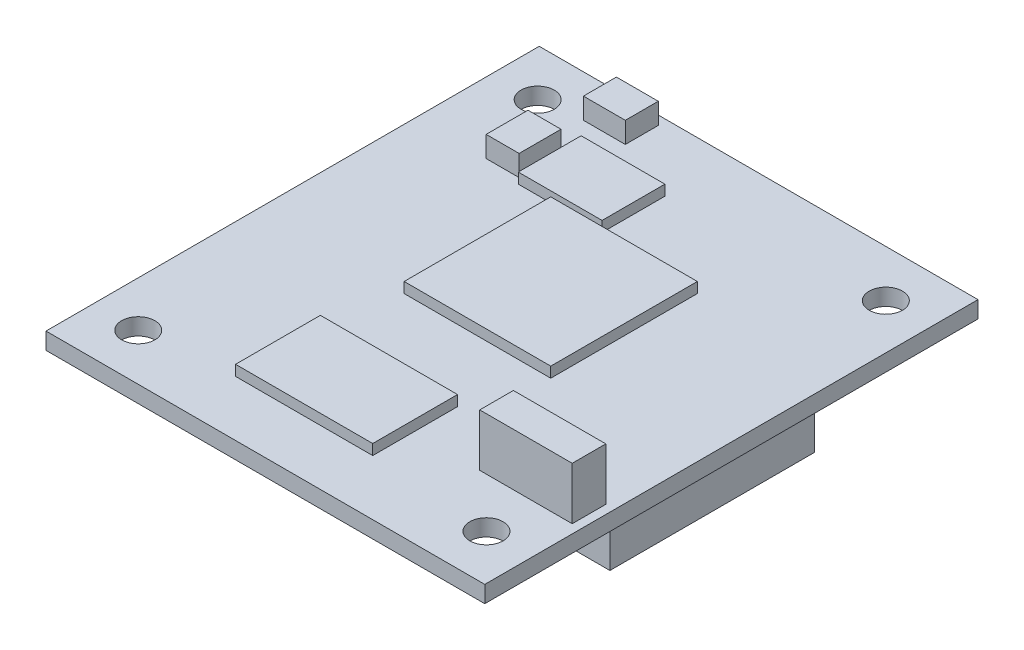
SolidWorks part; units mm, degrees
ref_plane "前视基准面" through (0, 0, 0) normal (0, 0, 1) x (1, 0, 0)
ref_plane "上视基准面" through (0, 0, 0) normal (0, 1, 0) x (1, 0, 0)
ref_plane "右视基准面" through (0, 0, 0) normal (1, 0, 0) x (0, 0, -1)
sketch "草图1" plane through (0, 0, 0) normal (0, 1, 0) x (1, 0, 0)
  line L0 (0, 4.47) -> (41.9, 4.47) construction
  line L1 (0, 0) -> (41.9, 0)
  line L2 (0, 0) -> (0, 47.1)
  line L3 (0, 47.1) -> (41.9, 47.1)
  line L4 (41.9, 0) -> (41.9, 47.1)
  line L5 (0, 42.61) -> (41.9, 42.61) construction
  line L6 (4.34, 47.1) -> (4.34, 0) construction
  line L7 (37.59, 47.1) -> (37.59, 0) construction
  circle A0 centre (4.34, 42.61) radius 1.5875
  circle A1 centre (37.59, 42.61) radius 1.5875
  circle A2 centre (37.59, 4.47) radius 1.5875
  circle A3 centre (4.34, 4.47) radius 1.5875
  dimension "D7" = 3.175
  dimension "D8" = 3.175
  dimension "D9" = 3.175
  dimension "D10" = 3.175
  dimension "D1" = 47.1
  dimension "D2" = 41.9
  dimension "D3" = 4.34
  dimension "D4" = 4.31
  dimension "D5" = 4.47
  dimension "D6" = 4.49
extrude "凸台-拉伸1" add sketch "草图1" along normal blind 1.6
sketch "草图2" plane through (0, 1.6, 0) normal (0, 1, 0) x (1, 0, 0)
  line L0 (0, 0) -> (41.9, 0) construction
  line L1 (6.75, 39.28) -> (9.9, 39.28)
  line L2 (6.75, 39.28) -> (6.75, 35.28)
  line L3 (6.75, 35.28) -> (9.9, 35.28)
  line L4 (9.9, 39.28) -> (9.9, 35.28)
  line L5 (0, 47.1) -> (0, 0) construction
  line L7 (8.23, 46.24) -> (12.23, 46.24)
  line L8 (8.23, 46.24) -> (8.23, 43.09)
  line L9 (8.23, 43.09) -> (12.23, 43.09)
  line L10 (12.23, 46.24) -> (12.23, 43.09)
  dimension "D1" = 35.28
  dimension "D2" = 6.75
  dimension "D3" = 3.15
  dimension "D4" = 4
  dimension "D5" = 1.48
  dimension "D6" = 3.81
  dimension "D7" = 3.15
  dimension "D8" = 4
extrude "凸台-拉伸2" add sketch "草图2" along normal blind 2
sketch "草图3" plane through (0, 1.6, 0) normal (0, 1, 0) x (1, 0, 0)
  line L0 (0, 47.1) -> (0, 0) construction
  line L1 (32.23, 12.4) -> (41.06, 12.4)
  line L2 (32.23, 12.4) -> (32.23, 9.19)
  line L3 (32.23, 9.19) -> (41.06, 9.19)
  line L4 (41.06, 12.4) -> (41.06, 9.19)
  line L5 (0, 0) -> (41.9, 0) construction
  dimension "D1" = 32.23
  dimension "D2" = 9.19
  dimension "D3" = 3.21
  dimension "D4" = 8.83
extrude "凸台-拉伸3" add sketch "草图3" along normal blind 5
sketch "草图4" plane through (0, 0, 0) normal (0, -1, 0) x (1, 0, 0)
  line L0 (0, -47.1) -> (0, 0) construction
  line L1 (1.77, -13.72) -> (6.54, -13.72)
  line L2 (1.77, -13.72) -> (1.77, -33.28)
  line L3 (1.77, -33.28) -> (6.54, -33.28)
  line L4 (6.54, -13.72) -> (6.54, -33.28)
  line L5 (35.36, -13.72) -> (40.13, -13.72)
  line L6 (35.36, -13.72) -> (35.36, -33.28)
  line L7 (35.36, -33.28) -> (40.13, -33.28)
  line L8 (40.13, -13.72) -> (40.13, -33.28)
  line L9 (41.9, 0) -> (41.9, -47.1) construction
  line L10 (41.9, -47.1) -> (0, -47.1) construction
  dimension "D1" = 1.77
  dimension "D2" = 1.77
  dimension "D3" = 13.82
  dimension "D4" = 13.82
  dimension "D5" = 4.77
  dimension "D6" = 4.77
  dimension "D7" = 19.56
  dimension "D8" = 19.56
extrude "凸台-拉伸4" add sketch "草图4" along normal blind 5
sketch "草图5" plane through (0, 1.6, 0) normal (0, 1, 0) x (1, 0, 0)
  line L0 (0, 47.1) -> (0, 0) construction
  line L1 (14, 34.2) -> (28, 34.2)
  line L2 (14, 34.2) -> (14, 20.2)
  line L3 (14, 20.2) -> (28, 20.2)
  line L4 (28, 34.2) -> (28, 20.2)
  line L5 (12.8, 13.4) -> (25.9, 13.4)
  line L6 (12.8, 13.4) -> (12.8, 5.3)
  line L7 (12.8, 5.3) -> (25.9, 5.3)
  line L8 (25.9, 13.4) -> (25.9, 5.3)
  line L9 (10.4, 40.7) -> (18.4, 40.7)
  line L10 (10.4, 40.7) -> (10.4, 34.7)
  line L11 (10.4, 34.7) -> (18.4, 34.7)
  line L12 (18.4, 40.7) -> (18.4, 34.7)
  line L13 (0, 0) -> (41.9, 0) construction
  line L14 (41.9, 47.1) -> (0, 47.1) construction
  dimension "D1" = 12.8
  dimension "D2" = 5.3
  dimension "D3" = 13.1
  dimension "D4" = 8.1
  dimension "D5" = 14
  dimension "D6" = 20.2
  dimension "D7" = 14
  dimension "D8" = 14
  dimension "D9" = 10.4
  dimension "D10" = 6.4
  dimension "D11" = 8
  dimension "D12" = 6
extrude "凸台-拉伸5" add sketch "草图5" along normal blind 1
